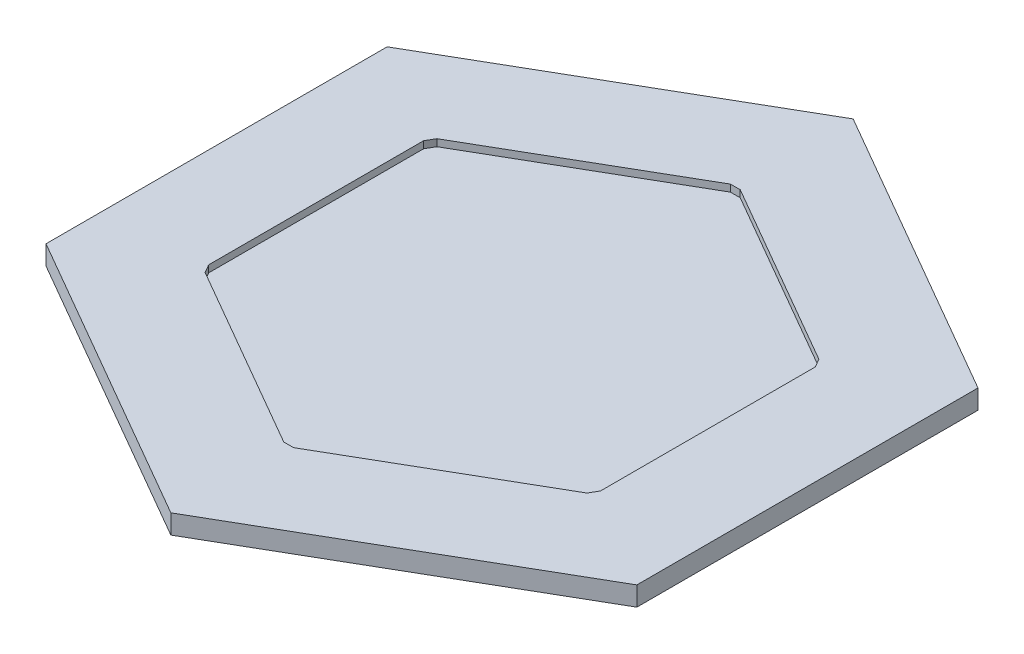
SolidWorks part; units mm, degrees
ref_plane "Front Plane" through (0, 0, 0) normal (0, 0, 1) x (1, 0, 0)
ref_plane "Top Plane" through (0, 0, 0) normal (0, 1, 0) x (1, 0, 0)
ref_plane "Right Plane" through (0, 0, 0) normal (1, 0, 0) x (0, 0, -1)
sketch "Sketch2" plane through (0, 0, 0) normal (0, 1, 0) x (-1, 0, 0)
  line L1 (1.1925, -54.404) -> (46.519, -28.2348)
  line L2 (47.7115, -26.1692) -> (47.7115, 26.1692)
  line L3 (46.519, 28.2348) -> (1.1925, 54.404)
  line L4 (-1.1925, 54.404) -> (-46.519, 28.2348)
  line L5 (-47.7115, 26.1692) -> (-47.7115, -26.1692)
  line L6 (-46.519, -28.2348) -> (-1.1925, -54.404)
  line L10 (-1.1925, 54.404) -> (1.1925, 54.404)
  line L12 (46.519, 28.2348) -> (47.7115, 26.1692)
  line L14 (47.7115, -26.1692) -> (46.519, -28.2348)
  line L16 (1.1925, -54.404) -> (-1.1925, -54.404)
  line L18 (-46.519, -28.2348) -> (-47.7115, -26.1692)
  line L20 (-47.7115, 26.1692) -> (-46.519, 28.2348)
  circle A0 centre (0, 0) radius 47.7115 construction
  point P13 (0, 0)
  point P14 (0, 0)
  point P15 (0, 0)
sketch "Sketch3" plane through (0, 0, 0) normal (0, 1, 0) x (1, 0, 0)
  line L0 (0, -83.094) -> (71.9615, -41.547)
  line L1 (0, -60) -> (51.9615, -30) construction
  line L2 (51.9615, -30) -> (51.9615, 30) construction
  line L3 (51.9615, 30) -> (0, 60) construction
  line L4 (0, 60) -> (-51.9615, 30) construction
  line L5 (-51.9615, 30) -> (-51.9615, -30) construction
  line L6 (-51.9615, -30) -> (0, -60) construction
  line L7 (71.9615, -41.547) -> (71.9615, 41.547)
  line L8 (71.9615, 41.547) -> (0, 83.094)
  line L9 (0, 83.094) -> (-71.9615, 41.547)
  line L10 (-71.9615, 41.547) -> (-71.9615, -41.547)
  line L11 (-71.9615, -41.547) -> (0, -83.094)
  line L36 (-1.1925, 54.404) -> (-46.519, 28.2348)
  line L37 (-46.519, 28.2348) -> (-47.7115, 26.1692)
  line L38 (-47.7115, 26.1692) -> (-47.7115, -26.1692)
  line L39 (-47.7115, -26.1692) -> (-46.519, -28.2348)
  line L40 (-46.519, -28.2348) -> (-1.1925, -54.404)
  line L41 (-1.1925, -54.404) -> (1.1925, -54.404)
  line L42 (1.1925, -54.404) -> (46.519, -28.2348)
  line L43 (46.519, -28.2348) -> (47.7115, -26.1692)
  line L44 (47.7115, -26.1692) -> (47.7115, 26.1692)
  line L45 (47.7115, 26.1692) -> (46.519, 28.2348)
  line L46 (46.519, 28.2348) -> (1.1925, 54.404)
  line L47 (1.1925, 54.404) -> (-1.1925, 54.404)
  line L60 (-1.1925, 54.404) -> (-46.519, 28.2348)
  line L61 (-46.519, 28.2348) -> (-47.7115, 26.1692)
  line L62 (-47.7115, 26.1692) -> (-47.7115, -26.1692)
  line L63 (-47.7115, -26.1692) -> (-46.519, -28.2348)
  line L64 (-46.519, -28.2348) -> (-1.1925, -54.404)
  line L65 (-1.1925, -54.404) -> (1.1925, -54.404)
  line L66 (1.1925, -54.404) -> (46.519, -28.2348)
  line L67 (46.519, -28.2348) -> (47.7115, -26.1692)
  line L68 (47.7115, -26.1692) -> (47.7115, 26.1692)
  line L69 (47.7115, 26.1692) -> (46.519, 28.2348)
  line L70 (46.519, 28.2348) -> (1.1925, 54.404)
  line L71 (1.1925, 54.404) -> (-1.1925, 54.404)
  circle A0 centre (0, 0) radius 60 construction
  point P15 (0, 0)
  point P16 (0, 0)
  point P17 (0, 0)
  dimension "D1" = 120
  dimension "D2" = 20
  dimension "D3" = 0
extrude "Boss-Extrude2" add sketch "Sketch3" along normal blind 1.7
sketch "Sketch6" plane through (0, 0, 0) normal (0, -1, 0) x (1, 0, 0)
  line L6 (0, 83.094) -> (-71.9615, 41.547)
  line L7 (-71.9615, 41.547) -> (-71.9615, -41.547)
  line L8 (-71.9615, -41.547) -> (0, -83.094)
  line L9 (0, -83.094) -> (71.9615, -41.547)
  line L10 (71.9615, -41.547) -> (71.9615, 41.547)
  line L11 (71.9615, 41.547) -> (0, 83.094)
  line L12 (0, 83.094) -> (-71.9615, 41.547)
  line L13 (-71.9615, 41.547) -> (-71.9615, -41.547)
  line L14 (-71.9615, -41.547) -> (0, -83.094)
  line L15 (0, -83.094) -> (71.9615, -41.547)
  line L16 (71.9615, -41.547) -> (71.9615, 41.547)
  line L17 (71.9615, 41.547) -> (0, 83.094)
  dimension "D1" = 0
extrude "Boss-Extrude3" add sketch "Sketch6" along normal blind 3
